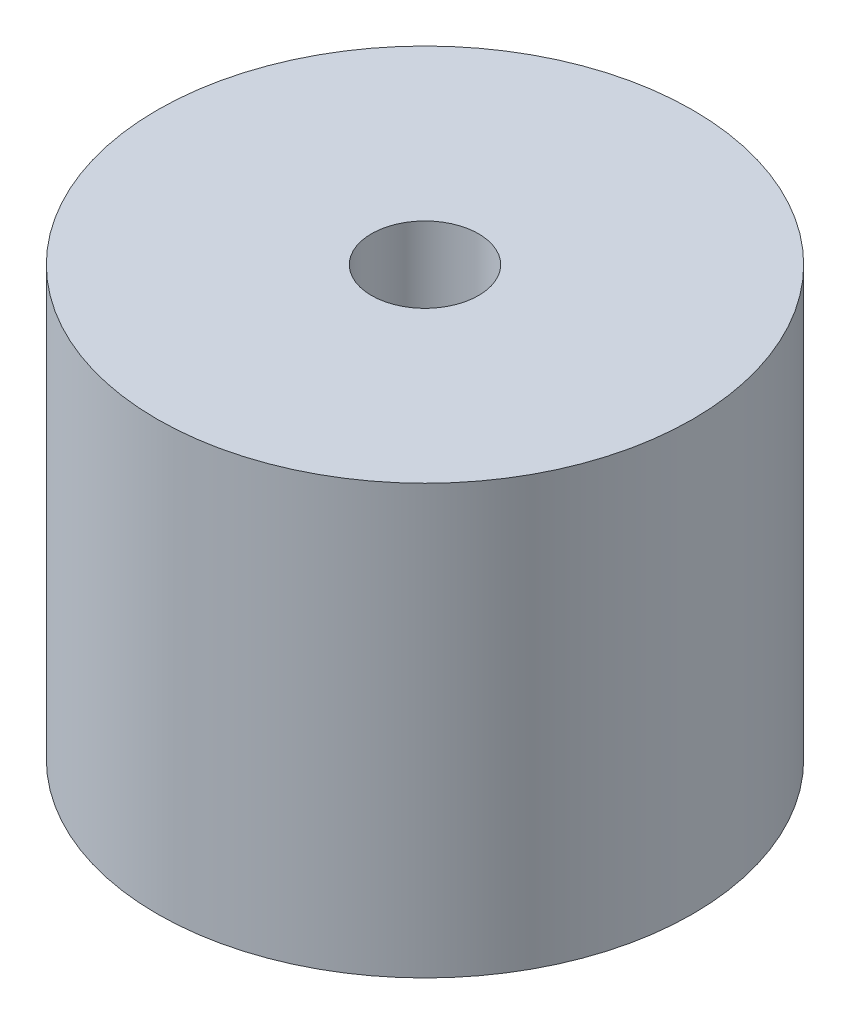
SolidWorks part; units mm, degrees
material "NBR"
ref_plane "Front Plane" through (0, 0, 0) normal (0, 0, 1) x (1, 0, 0)
ref_plane "Top Plane" through (0, 0, 0) normal (0, 1, 0) x (1, 0, 0)
ref_plane "Right Plane" through (0, 0, 0) normal (1, 0, 0) x (0, 0, -1)
sketch "Sketch1" plane through (0, 0, 0) normal (0, 1, 0) x (1, 0, 0)
  circle A0 centre (-6.3147, 6.4463) radius 12.5
  circle A1 centre (-6.3147, 6.4463) radius 2.5
  dimension "D1" = 25
  dimension "D2" = 5
extrude "Boss-Extrude1" add sketch "Sketch1" along normal blind 20
